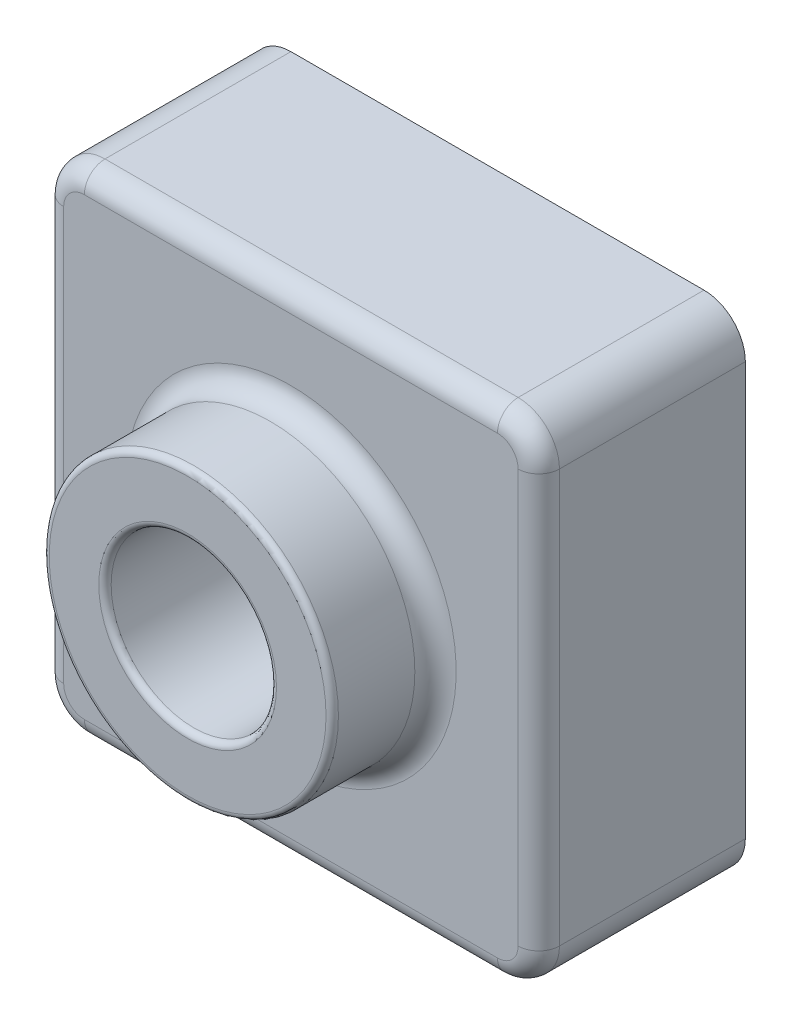
SolidWorks part; units mm, degrees
material "Chrome Stainless Steel"
ref_plane "Front Plane" through (0, 0, 0) normal (0, 0, 1) x (1, 0, 0)
ref_plane "Top Plane" through (0, 0, 0) normal (0, 1, 0) x (1, 0, 0)
ref_plane "Right Plane" through (0, 0, 0) normal (1, 0, 0) x (0, 0, -1)
sketch "Sketch1" plane through (0, 0, 0) normal (0, 0, 1) x (1, 0, 0)
  line L1 (0, 0) -> (120, 0)
  line L2 (0, 0) -> (0, 120)
  line L3 (0, 120) -> (120, 120)
  line L4 (120, 0) -> (120, 120)
  dimension "D1" = 120
  dimension "D2" = 120
extrude "Boss-Extrude1" add sketch "Sketch1" along normal blind 50
sketch "Sketch2" plane through (0, 0, 50) normal (0, 0, 1) x (1, 0, 0)
  line L0 (120, 120) -> (0, 120) construction
  line L1 (120, 0) -> (120, 120) construction
  circle A0 centre (60, 60) radius 35
  dimension "D1" = 70
  dimension "D2" = 60
  dimension "D3" = 60
extrude "Boss-Extrude2" add sketch "Sketch2" along normal blind 25
sketch "Sketch5" plane through (0, 0, 75) normal (0, 0, 1) x (1, 0, 0)
  circle A0 centre (60, 60) radius 20.0101
extrude "Cut-Extrude1" cut sketch "Sketch5" against normal through all contours A0
fillet "Fillet1" radius 10 4 edges at (0, 0, 25) (0, 120, 25) (120, 0, 25) (120, 120, 25)
fillet "Fillet2" radius 1.5 2 edges at (95, 60, 75) (80.0101, 60, 75)
fillet "Fillet3" radius 5 9 edges at (2.9289, 117.0711, 50) (60, 120, 50) (117.0711, 117.0711, 50) (120, 60, 50) (117.0711, 2.9289, 50) (60, 0, 50) (2.9289, 2.9289, 50) (0, 60, 50) (95, 60, 50)
shell "Shell1" thickness 2
